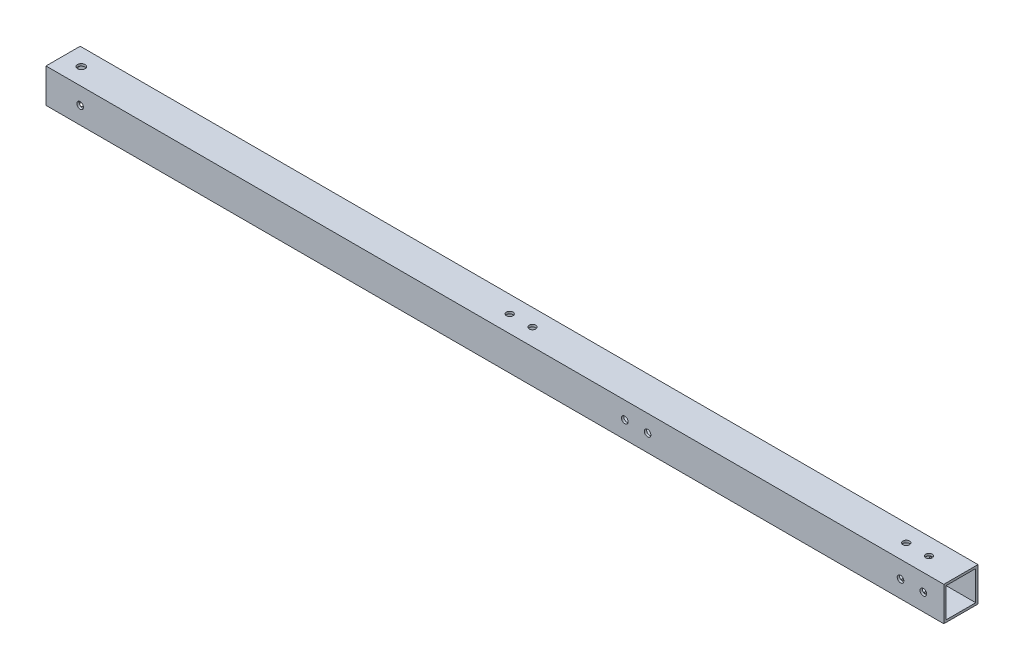
SolidWorks part; units mm, degrees
material "Thornel Mat VMA"
ref_plane "前视基准面" through (0, 0, 0) normal (0, 0, 1) x (1, 0, 0)
ref_plane "上视基准面" through (0, 0, 0) normal (0, 1, 0) x (1, 0, 0)
ref_plane "右视基准面" through (0, 0, 0) normal (1, 0, 0) x (0, 0, -1)
other "Configuration Table"
sketch "草图1" plane through (0, 0, 0) normal (1, 0, 0) x (0, 0, -1)
  line L0 (-6.5, -6.5) -> (-6.5, 6.5)
  line L1 (-7.5, -7.5) -> (7.5, -7.5)
  line L2 (-7.5, -7.5) -> (-7.5, 7.5)
  line L3 (-7.5, 7.5) -> (7.5, 7.5)
  line L4 (7.5, -7.5) -> (7.5, 7.5)
  line L5 (-7.5, -7.5) -> (7.5, 7.5) construction
  line L6 (-7.5, 7.5) -> (7.5, -7.5) construction
  line L7 (-6.5, 6.5) -> (6.5, 6.5)
  line L8 (6.5, -6.5) -> (6.5, 6.5)
  line L9 (-6.5, -6.5) -> (6.5, -6.5)
  point P0 (0, 0)
  dimension "D1" = 15
  dimension "D2" = 15
  dimension "D3" = 1
extrude "凸台-拉伸1" add sketch "草图1" along normal blind 394
sketch "草图2" plane through (0, 7.5, 0) normal (0, 1, 0) x (1, 0, 0)
  circle A1 centre (380, 0) radius 1.45 construction
  circle A2 centre (370, 0) radius 1.45 construction
  circle A3 centre (196, 0) radius 1.45 construction
  circle A4 centre (206, 0) radius 1.45 construction
  circle A6 centre (380, 0) radius 1.45
  circle A7 centre (370, 0) radius 1.45
  circle A8 centre (196, 0) radius 1.45
  circle A9 centre (206, 0) radius 1.45
  circle A10 centre (8, 0) radius 1.65 construction
  circle A11 centre (8, 0) radius 1.65
extrude "切除-拉伸1" cut sketch "草图2" against normal through all
sketch "草图3" plane through (0, 0, 7.5) normal (0, 0, 1) x (1, 0, 0)
  line L0 (394, 7.5) -> (0, 7.5) construction
  circle A0 centre (375, 0) radius 1.45 construction
  circle A1 centre (385, 0) radius 1.45 construction
  circle A2 centre (375, 0) radius 1.45
  circle A3 centre (385, 0) radius 1.45
  circle A4 centre (264, 0) radius 1.45 construction
  circle A5 centre (254, 0) radius 1.45 construction
  circle A6 centre (264, 0) radius 1.45
  circle A7 centre (254, 0) radius 1.45
  circle A8 centre (15, 0) radius 1.45
  dimension "D1" = 239
  dimension "D2" = 2.9
  dimension "D3" = 7.5
extrude "切除-拉伸2" cut sketch "草图3" against normal through all
